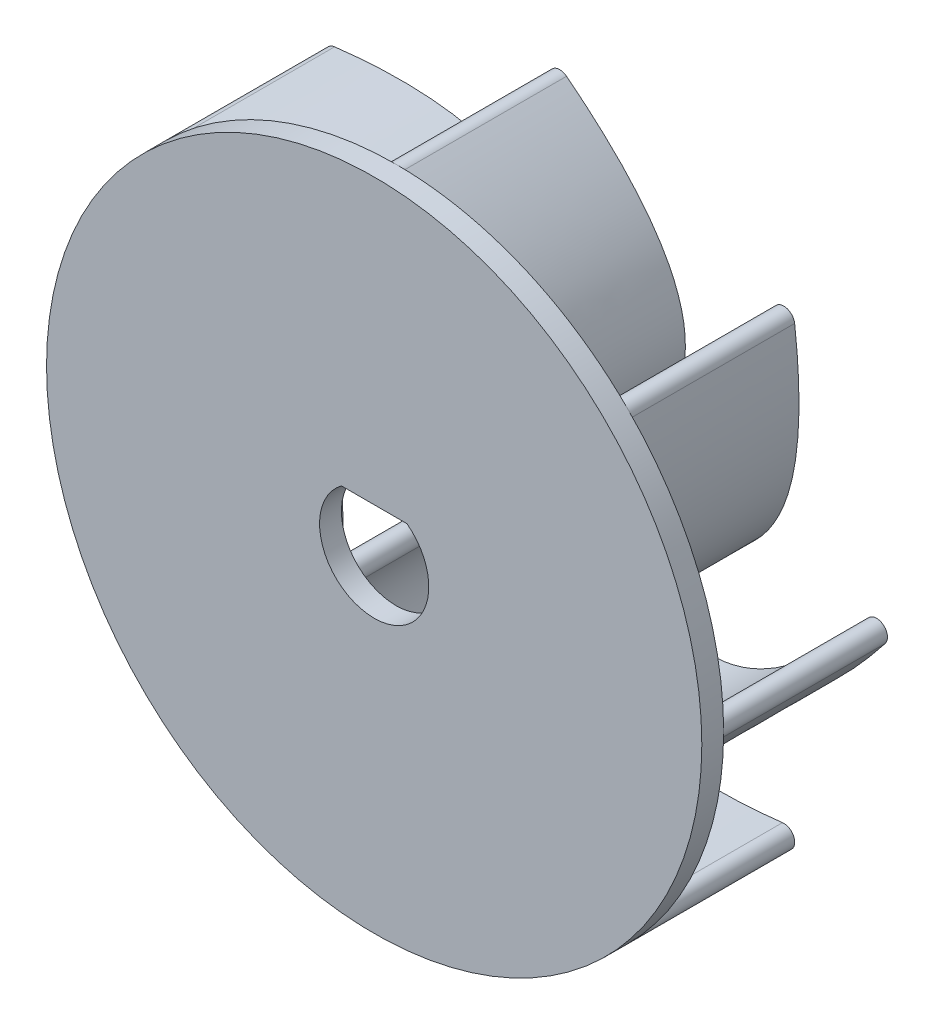
SolidWorks part; units mm, degrees
ref_plane "前视基准面" through (0, 0, 0) normal (0, 0, 1) x (1, 0, 0)
ref_plane "上视基准面" through (0, 0, 0) normal (0, 1, 0) x (1, 0, 0)
ref_plane "右视基准面" through (0, 0, 0) normal (1, 0, 0) x (0, 0, -1)
other "Configuration Table"
sketch "草图1" plane through (0, 0, 0) normal (0, 0, 1) x (1, 0, 0)
  line L0 (-3, 4) -> (3, 4)
  circle A0 centre (0, 0) radius 30
  circle A1 centre (0, 0) radius 5
  dimension "D1" = 60
  dimension "D2" = 10
  dimension "D3" = 4
extrude "凸台-拉伸1" add sketch "草图1" along normal blind 2 contours A0 A1 | L0 A1
sketch "草图2" plane through (0, 0, 2) normal (0, 0, 1) x (1, 0, 0)
  line L0 (0, -5) -> (0, -30) construction
  line L1 (0, 0) -> (20.5061, -20.5061) construction
  line L2 (0, -13) -> (1.842, -19.8746) construction
  line L3 (0, -13) -> (2.5882, -22.6593) construction
  line L4 (2.5882, -22.6593) -> (20.5061, -20.5061) construction
  circle A0 centre (0, 0) radius 5 construction
  circle A1 centre (0, 0) radius 30 construction
  circle A2 centre (0, 0) radius 13 construction
  arc A4 (20.6254, -21.499) -> (20.3868, -19.5132) centre (20.5061, -20.5061) ccw
  arc A5 (-0.9659, -13.2588) -> (0.9659, -12.7412) centre (0, -13) cw
  spline S0 degree 2 poles (0, -13) (2.5882, -22.6593) (20.5061, -20.5061) knots 0 0 0 1 1 1 construction
  spline S1 degree 1 poles (-0.9659, -13.2588) (20.6254, -21.499) knots 0 0 1 1 construction
  spline S2 degree 2 poles (-0.9659, -13.2588) (-0.4389, -15.2401) (1.8472, -18.3565) (5.8529, -20.8549) (13.8151, -22.3276) (20.6254, -21.499) knots 0 0 0 0.1875 0.375 0.625 1 1 1
  spline S3 degree 1 poles (0.9659, -12.7412) (20.3868, -19.5132) knots 0 0 1 1 construction
  spline S4 degree 2 poles (0.9659, -12.7412) (1.4095, -14.3821) (3.2203, -16.8491) (6.5093, -18.9266) (13.7587, -20.2995) (20.3868, -19.5132) knots 0 0 0 0.1875 0.375 0.625 1 1 1
  dimension "D2" = 26
  dimension "D1" = 45
  dimension "D3" = 15
  dimension "D4" = 10
  dimension "D5" = 1
  dimension "D6" = 1
extrude "凸台-拉伸2" add sketch "草图2" against normal blind 17 contours S4 A4 S2 A5
pattern_circular "阵列(圆周)1" count 8 over 360 of "凸台-拉伸2"
